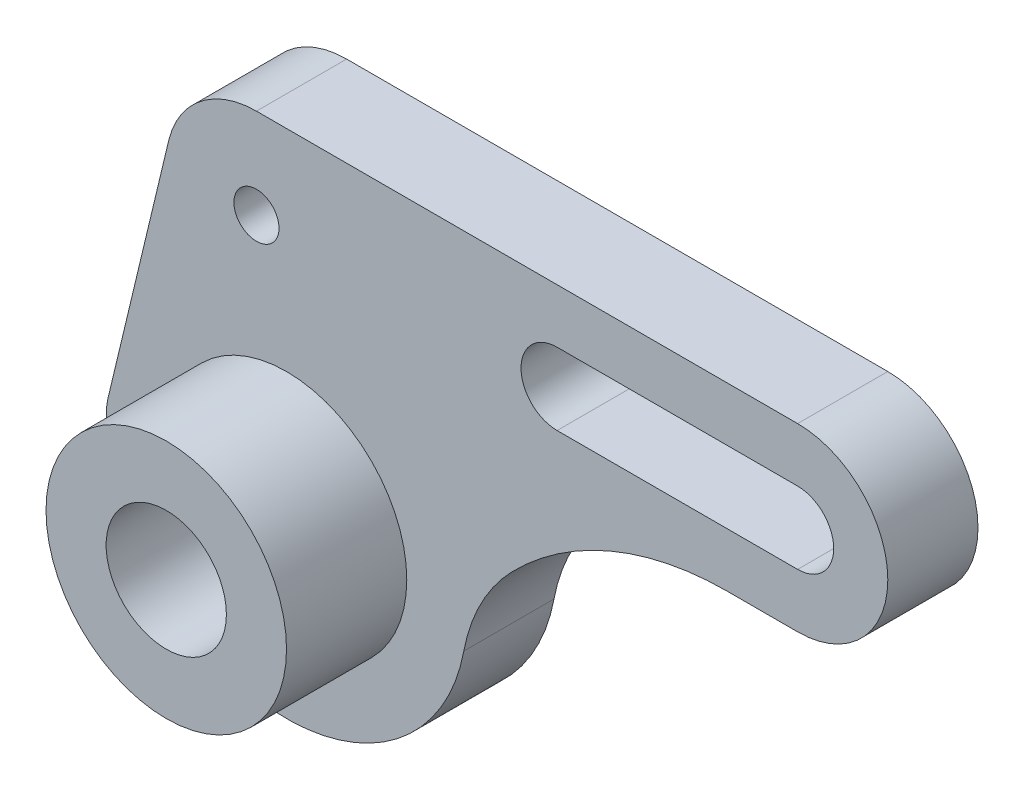
SolidWorks part; units mm, degrees
ref_plane "Front Plane" through (0, 0, 0) normal (0, 0, 1) x (1, 0, 0)
ref_plane "Top Plane" through (0, 0, 0) normal (0, 1, 0) x (1, 0, 0)
ref_plane "Right Plane" through (0, 0, 0) normal (1, 0, 0) x (0, 0, -1)
sketch "Sketch1" plane through (0, 0, 0) normal (0, 0, 1) x (1, 0, 0)
  line L0 (0, 20.3916) -> (0, -15.4327) construction
  line L1 (-1.25, 40) -> (-8.75, 40) construction
  line L2 (30, 0) -> (-30, 0) construction
  line L3 (45, 40) -> (85, 40) construction
  line L4 (45, 46) -> (85, 46)
  line L5 (45, 34) -> (85, 34)
  line L6 (45, 40) -> (85, 40) construction
  line L7 (45, 55) -> (85, 55)
  line L8 (73.3013, 25) -> (85, 25)
  line L9 (45, 55) -> (-5, 55)
  line L11 (-29.697, 1.2658) -> (-19.5878, 43.4924)
  arc A0 (-29.9576, -1.5936) -> (29.4873, -5.5224) centre (0, 0) ccw
  circle A1 centre (-5, 40) radius 3.75
  arc A2 (-5, 55) -> (-19.5878, 43.4924) centre (-5, 40) ccw
  arc A3 (45, 46) -> (45, 34) centre (45, 40) ccw
  arc A4 (85, 34) -> (85, 46) centre (85, 40) ccw
  arc A6 (85, 25) -> (85, 55) centre (85, 40) ccw
  arc A9 (37.4848, 9.8881) -> (29.4873, -5.5224) centre (58.9747, -11.0448) ccw
  arc A10 (73.3013, 25) -> (37.4848, 9.8881) centre (73.3013, -25) ccw
  arc A11 (-29.697, 1.2658) -> (-29.9576, -1.5936) centre (-19.9718, -1.0624) ccw
  point P14 (65, 40)
  point P21 (65, 40)
  dimension "D1" = 40
  dimension "D3" = 40
  dimension "D5" = 6
  dimension "D6" = 15
  dimension "D7" = 60
  dimension "D8" = 30
  dimension "D9" = 7.5
  dimension "D10" = 10
  dimension "D2" = 5
  dimension "D4" = 50
extrude "Boss-Extrude1" add sketch "Sketch1" along normal blind 15
sketch "Sketch2" plane through (0, 0, 15) normal (0, 0, 1) x (1, 0, 0)
  circle A1 centre (0, 0) radius 20
extrude "Boss-Extrude2" add sketch "Sketch2" along normal blind 20
sketch "Sketch4" plane through (0, 0, 35) normal (0, 0, 1) x (1, 0, 0)
  circle A0 centre (0, 0) radius 10
extrude "Cut-Extrude1" cut sketch "Sketch4" against normal up to surface (35 mm away) up to face at (-1.25, 40, 0)
